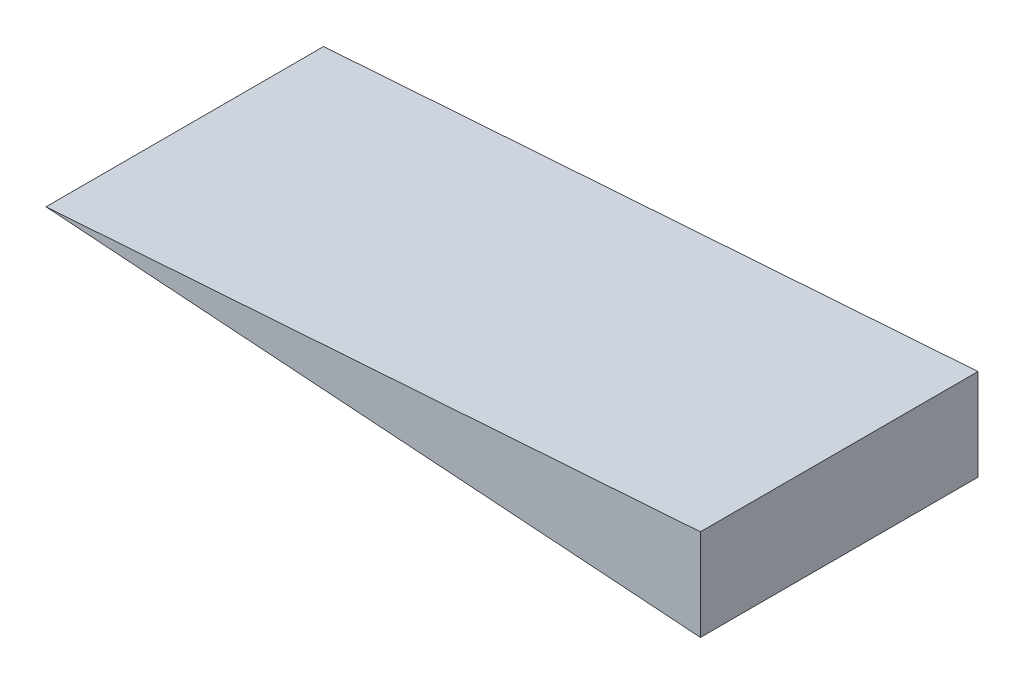
SolidWorks part; units mm, degrees
ref_plane "Front Plane" through (0, 0, 0) normal (0, 0, 1) x (1, 0, 0)
ref_plane "Top Plane" through (0, 0, 0) normal (0, 1, 0) x (1, 0, 0)
ref_plane "Right Plane" through (0, 0, 0) normal (1, 0, 0) x (0, 0, -1)
sketch "Sketch1" plane through (0, 0, 0) normal (0, 0, 1) x (1, 0, 0)
  line L0 (-35.7517, 0) -> (200, 16.4854) construction
  line L1 (-35.7517, 0) -> (200, -16.4854) construction
  line L2 (0, 2.5) -> (0, -2.5) construction
  line L3 (200, 16.4854) -> (200, -16.4854) construction
  point P5 (200, 0)
  point P6 (0, 0)
  dimension "D1" = 5
  dimension "D2" = 8
  dimension "D3" = 200
ref_plane "Plane1" through (-0.174, 2.4878, 0) normal (0.0698, -0.9976, 0) x (0.9976, 0.0698, 0)
ref_plane "Plane2" through (-0.174, -2.4878, 0) normal (-0.0698, -0.9976, 0) x (0.9976, -0.0698, 0)
ref_plane "Plane3" through (200, 0, 0) normal (1, 0, 0) x (0, 0, -1)
sketch "Sketch2" plane through (-0.174, 2.4878, 0) normal (0.0698, -0.9976, 0) x (0.9976, 0.0698, 0)
  line L1 (-35.6646, 50) -> (200.6628, 50)
  line L2 (-35.6646, 50) -> (-35.6646, -50)
  line L3 (-35.6646, -50) -> (200.6628, -50)
  line L4 (200.6628, 50) -> (200.6628, -50)
  point P4 (-35.6646, 0)
  dimension "D1" = 100
sketch "Sketch3" plane through (-0.174, -2.4878, 0) normal (-0.0698, -0.9976, 0) x (0.9976, -0.0698, 0)
  line L1 (200.6628, 50) -> (-35.6646, 50)
  line L2 (200.6628, 50) -> (200.6628, -50)
  line L3 (200.6628, -50) -> (-35.6646, -50)
  line L4 (-35.6646, 50) -> (-35.6646, -50)
  point P4 (-35.6646, 0)
  dimension "D1" = 100
sketch "Sketch4" plane through (200, 0, 0) normal (1, 0, 0) x (0, 0, -1)
  line L0 (-50, 16.4854) -> (50, 16.4854) construction
  line L1 (-50, 16.4854) -> (50, 16.4854)
  line L2 (-50, 16.4854) -> (-50, -16.4854)
  line L3 (-50, -16.4854) -> (50, -16.4854)
  line L4 (50, 16.4854) -> (50, -16.4854)
  line L5 (-50, 0) -> (-50, 16.4854) construction
  line L6 (-50, -16.4854) -> (50, -16.4854) construction
  line L7 (50, -16.4854) -> (50, 0) construction
ref_plane "Plane4" through (0, 0, -50) normal (0, 0, 1) x (1, 0, 0)
ref_plane "Plane5" through (0, 0, 50) normal (0, 0, 1) x (1, 0, 0)
sketch "Sketch5" plane through (0, 0, -50) normal (0, 0, 1) x (1, 0, 0)
  line L0 (-35.7517, 0) -> (200, 16.4854)
  line L1 (200, 16.4854) -> (200, -16.4854)
  line L2 (200, -16.4854) -> (-35.7517, 0)
sketch "Sketch7" plane through (0, 0, 50) normal (0, 0, 1) x (1, 0, 0)
  line L0 (-35.7517, 0) -> (200, 16.4854)
  line L1 (200, 16.4854) -> (200, -16.4854)
  line L2 (200, -16.4854) -> (-35.7517, 0)
surface "Surface-Plane1" sketch "Sketch2"
surface "Surface-Plane2" sketch "Sketch3"
surface "Surface-Plane3" sketch "Sketch7"
surface "Surface-Plane4" sketch "Sketch4"
surface "Surface-Plane5" sketch "Sketch5"
surface "Surface-Knit1"
